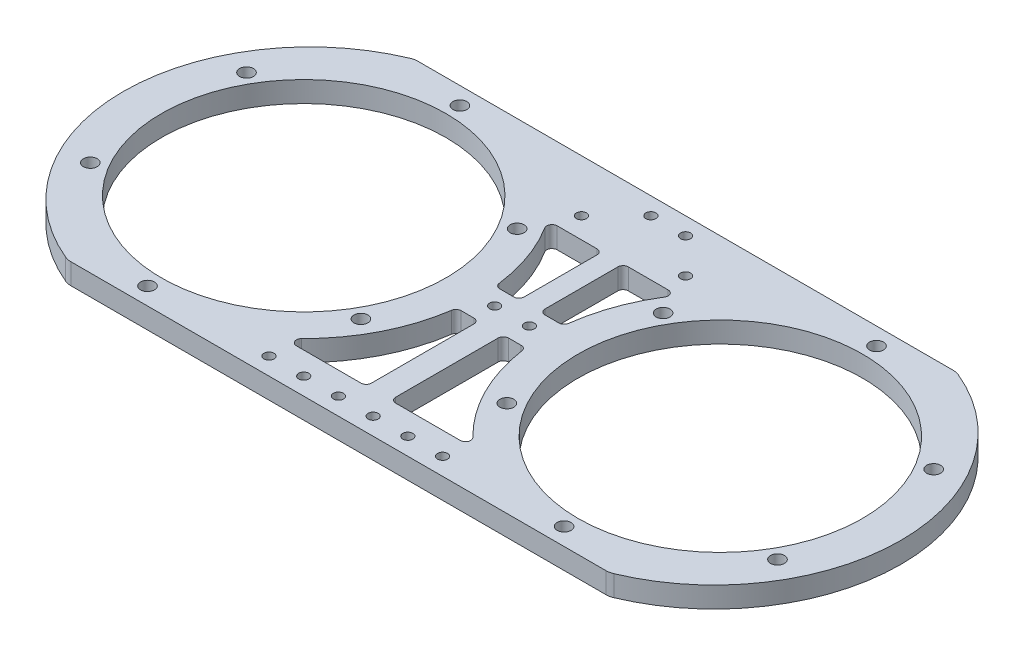
SolidWorks part; units mm, degrees
ref_plane "前视基准面" through (0, 0, 0) normal (0, 0, 1) x (1, 0, 0)
ref_plane "上视基准面" through (0, 0, 0) normal (0, 1, 0) x (1, 0, 0)
ref_plane "右视基准面" through (0, 0, 0) normal (1, 0, 0) x (0, 0, -1)
sketch "草图1" plane through (0, 0, 0) normal (0, 1, 0) x (1, 0, 0)
  line L0 (0, 0) -> (67.2377, 0) construction
  line L1 (0, 53.3081) -> (0, -9.8086) construction
  line L2 (30, 50) -> (10, 50) construction
  line L3 (60, -45) -> (98.9711, -22.5) construction
  line L4 (98.9711, -22.5) -> (98.9711, 22.5) construction
  line L5 (98.9711, 22.5) -> (60, 45) construction
  line L6 (60, 45) -> (21.0289, 22.5) construction
  line L7 (21.0289, 22.5) -> (21.0289, -22.5) construction
  line L8 (21.0289, -22.5) -> (60, -45) construction
  line L9 (-10, 50) -> (10, 50) construction
  line L10 (-10, 50) -> (-10, -50) construction
  line L11 (-10, -50) -> (10, -50) construction
  line L12 (10, 50) -> (10, -50) construction
  line L13 (-10, 50) -> (10, -50) construction
  line L14 (-10, -50) -> (10, 50) construction
  line L15 (30, -40) -> (10, -40) construction
  line L16 (30, -40) -> (30, -50) construction
  line L17 (30, -50) -> (10, -50) construction
  line L18 (10, -40) -> (10, -50) construction
  line L19 (30, -40) -> (10, -50) construction
  line L20 (30, -50) -> (10, -40) construction
  line L21 (10, 40) -> (10, 50) construction
  line L22 (30, 40) -> (10, 40) construction
  line L23 (30, 40) -> (30, 50) construction
  line L24 (-30, -50) -> (-10, -50) construction
  line L25 (-10, -40) -> (-10, -50) construction
  line L26 (-30, -40) -> (-10, -40) construction
  line L27 (-30, -40) -> (-30, -50) construction
  line L28 (-30, 40) -> (-30, 50) construction
  line L29 (-30, 40) -> (-10, 40) construction
  line L30 (-10, 40) -> (-10, 50) construction
  line L31 (-30, 50) -> (-10, 50) construction
  line L32 (-77.0235, 50) -> (77.0235, 50)
  line L33 (78, -50) -> (78, -40) construction
  line L34 (75, 50) -> (78, 50) construction
  line L35 (75, 50) -> (75, 40) construction
  line L36 (75, 40) -> (78, 40) construction
  line L37 (78, 50) -> (78, 40) construction
  line L38 (75, 50) -> (78, 40) construction
  line L39 (75, 40) -> (78, 50) construction
  line L40 (75, -50) -> (75, -40) construction
  line L41 (75, -40) -> (78, -40) construction
  line L42 (-77.0235, -50) -> (77.0235, -50)
  line L43 (-75, 50) -> (-75, 40) construction
  line L44 (-75, 40) -> (-78, 40) construction
  line L45 (-78, 50) -> (-78, 40) construction
  line L46 (-78, -50) -> (-78, -40) construction
  line L47 (-75, -40) -> (-78, -40) construction
  line L48 (-75, -50) -> (-75, -40) construction
  line L49 (20, 30) -> (10, 30) construction
  line L50 (-5, 45) -> (5, 45) construction
  line L51 (-5, 45) -> (-5, -45) construction
  line L52 (-5, -45) -> (5, -45) construction
  line L53 (5, 45) -> (5, -45) construction
  line L54 (-5, 45) -> (5, -45) construction
  line L55 (-5, -45) -> (5, 45) construction
  line L56 (-20, 30) -> (-10, 30) construction
  line L57 (-20, 30) -> (-20, 40) construction
  line L58 (-20, 40) -> (-10, 40) construction
  line L59 (-10, 30) -> (-10, 40) construction
  line L60 (-20, 30) -> (-10, 40) construction
  line L61 (-20, 40) -> (-10, 30) construction
  line L62 (20, 30) -> (20, 40) construction
  line L63 (-3.5, -7.5) -> (-3.5, -37)
  line L64 (-5, -38.5) -> (-23.6048, -38.5)
  line L65 (-5, -6) -> (-8.6448, -6)
  line L66 (5, -6) -> (8.6448, -6)
  line L67 (3.5, -7.5) -> (3.5, -37)
  line L68 (5, -38.5) -> (23.6048, -38.5)
  line L69 (-15.9845, 29) -> (-4.5, 29)
  line L70 (-3, 27.5) -> (-3, 6.5)
  line L71 (-4.5, 5) -> (-8.5086, 5)
  line L72 (15.9845, 29) -> (4.5, 29)
  line L73 (3, 27.5) -> (3, 6.5)
  line L74 (4.5, 5) -> (8.5086, 5)
  circle A0 centre (60, 0) radius 45 construction
  circle A1 centre (60, 0) radius 38.9711 construction
  circle A2 centre (60, 45) radius 2
  circle A3 centre (21.0289, 22.5) radius 2
  circle A4 centre (21.0289, -22.5) radius 2
  circle A5 centre (60, -45) radius 2
  circle A6 centre (98.9711, -22.5) radius 2
  circle A7 centre (98.9711, 22.5) radius 2
  circle A8 centre (60, 0) radius 41
  circle A9 centre (60, 0) radius 48.9 construction
  circle A10 centre (-60, 0) radius 45 construction
  circle A11 centre (-60, 0) radius 48.9 construction
  circle A12 centre (-60, 0) radius 41
  circle A13 centre (-21.0289, -22.5) radius 2
  circle A14 centre (-21.0289, 22.5) radius 2
  circle A15 centre (-60, 45) radius 2
  circle A16 centre (-98.9711, 22.5) radius 2
  circle A17 centre (-98.9711, -22.5) radius 2
  circle A18 centre (-60, -45) radius 2
  arc A19 (78.9499, 49.614) -> (78.9499, -49.614) centre (58.2353, 0) cw
  arc A20 (-78.9499, 49.614) -> (-78.9499, -49.614) centre (-58.2353, 0) ccw
  arc A21 (-77.0235, -50) -> (-78.9499, -49.614) centre (-77.0235, -45) cw
  arc A22 (-77.0235, 50) -> (-78.9499, 49.614) centre (-77.0235, 45) ccw
  arc A23 (78.9499, -49.614) -> (77.0235, -50) centre (77.0235, -45) cw
  arc A24 (77.0235, 50) -> (78.9499, 49.614) centre (77.0235, 45) cw
  circle A25 centre (-5, 45) radius 1.45
  circle A26 centre (5, 45) radius 1.45
  circle A27 centre (-5, 0) radius 1.45
  circle A28 centre (5, 0) radius 1.45
  circle A29 centre (-5, -45) radius 1.45
  circle A30 centre (5, -45) radius 1.45
  circle A34 centre (-15, 35) radius 1.45
  circle A35 centre (15, 35) radius 1.45
  circle A36 centre (-15, -45) radius 1.45
  circle A37 centre (-25, -45) radius 1.45
  circle A38 centre (25, -45) radius 1.45
  circle A39 centre (15, -45) radius 1.45
  arc A40 (-10.129, -7.2832) -> (-24.6567, -35.9306) centre (-60, 0) cw
  arc A41 (-23.6048, -38.5) -> (-24.6567, -35.9306) centre (-23.6048, -37) cw
  arc A42 (-3.5, -37) -> (-5, -38.5) centre (-5, -37) cw
  arc A43 (-3.5, -7.5) -> (-5, -6) centre (-5, -7.5) ccw
  arc A44 (-8.6448, -6) -> (-10.129, -7.2832) centre (-8.6448, -7.5) ccw
  arc A45 (3.5, -7.5) -> (5, -6) centre (5, -7.5) cw
  arc A46 (3.5, -37) -> (5, -38.5) centre (5, -37) ccw
  arc A47 (23.6048, -38.5) -> (24.6567, -35.9306) centre (23.6048, -37) ccw
  arc A48 (8.6448, -6) -> (10.129, -7.2832) centre (8.6448, -7.5) cw
  arc A49 (10.129, -7.2832) -> (24.6567, -35.9306) centre (60, 0) ccw
  arc A50 (-17.2567, 26.7052) -> (-9.9968, 6.3121) centre (-60, 0) cw
  arc A51 (-4.5, 29) -> (-3, 27.5) centre (-4.5, 27.5) cw
  arc A52 (-3, 6.5) -> (-4.5, 5) centre (-4.5, 6.5) cw
  arc A53 (-8.5086, 5) -> (-9.9968, 6.3121) centre (-8.5086, 6.5) cw
  arc A54 (-15.9845, 29) -> (-17.2567, 26.7052) centre (-15.9845, 27.5) ccw
  arc A55 (4.5, 29) -> (3, 27.5) centre (4.5, 27.5) ccw
  arc A56 (3, 6.5) -> (4.5, 5) centre (4.5, 6.5) ccw
  arc A57 (8.5086, 5) -> (9.9968, 6.3121) centre (8.5086, 6.5) ccw
  arc A58 (15.9845, 29) -> (17.2567, 26.7052) centre (15.9845, 27.5) cw
  arc A59 (17.2567, 26.7052) -> (9.9968, 6.3121) centre (60, 0) ccw
  point P23 (11.1, 0)
  point P24 (0, 0)
  point P29 (20, -45)
  point P30 (0, 0)
  point P34 (76.5, 45)
  point P65 (112, 0)
  point P68 (105, 0)
  point P80 (0, -50)
  point P81 (0, 50)
  point P105 (-15, 35)
  dimension "D1" = 90
  dimension "D3" = 4
  dimension "D4" = 82
  dimension "D5" = 97.8
  dimension "D14" = 5
  dimension "D17" = 2.9
  dimension "D22" = 1.5
  dimension "D23" = 1.5
  dimension "D27" = 1.5
  dimension "D28" = 1.5
  dimension "D32" = 1.5
  dimension "D33" = 1.5
  dimension "D2" = 60
  dimension "D6" = 20
  dimension "D7" = 100
  dimension "D8" = 20
  dimension "D9" = 10
  dimension "D10" = 10
  dimension "D11" = 3
  dimension "D12" = 15
  dimension "D13" = 7
  dimension "D15" = 10
  dimension "D16" = 5
  dimension "D18" = 10
  dimension "D19" = 10
  dimension "D20" = 5
  dimension "D21" = 5
  dimension "D24" = 3.5
  dimension "D25" = 6
  dimension "D26" = 1.5
  dimension "D29" = 5
  dimension "D30" = 1
  dimension "D31" = 3
extrude "凸台-拉伸1" add sketch "草图1" along normal blind 6
